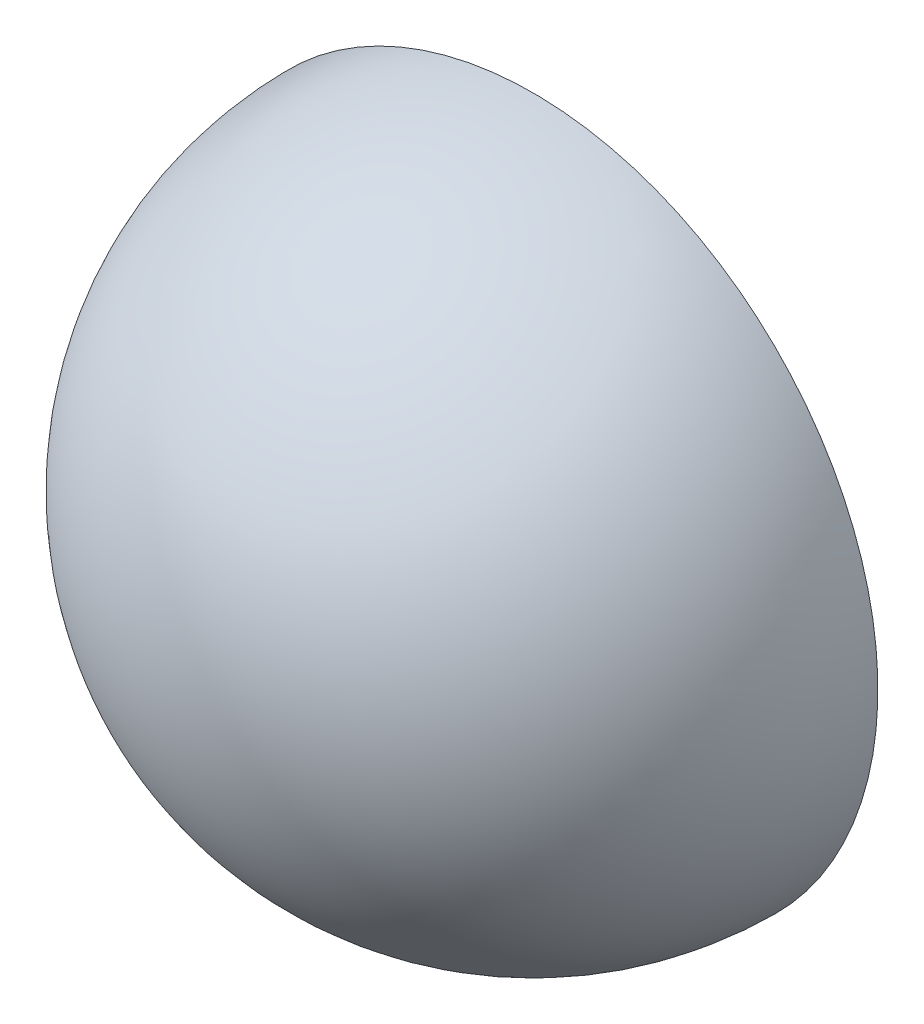
SolidWorks part; units mm, degrees
ref_plane "前视基准面" through (0, 0, 0) normal (0, 0, 1) x (1, 0, 0)
ref_plane "上视基准面" through (0, 0, 0) normal (0, 1, 0) x (1, 0, 0)
ref_plane "右视基准面" through (0, 0, 0) normal (1, 0, 0) x (0, 0, -1)
sketch "草图1" plane through (0, 0, 0) normal (0, 0, 1) x (1, 0, 0)
  line L0 (0, 2.5) -> (0, -2.5)
  arc A0 (0, -2.5) -> (0, 2.5) centre (0, 0) ccw
  dimension "D1" = 2.5
revolve "旋转1" add sketch "草图1" angle 180 about L0
